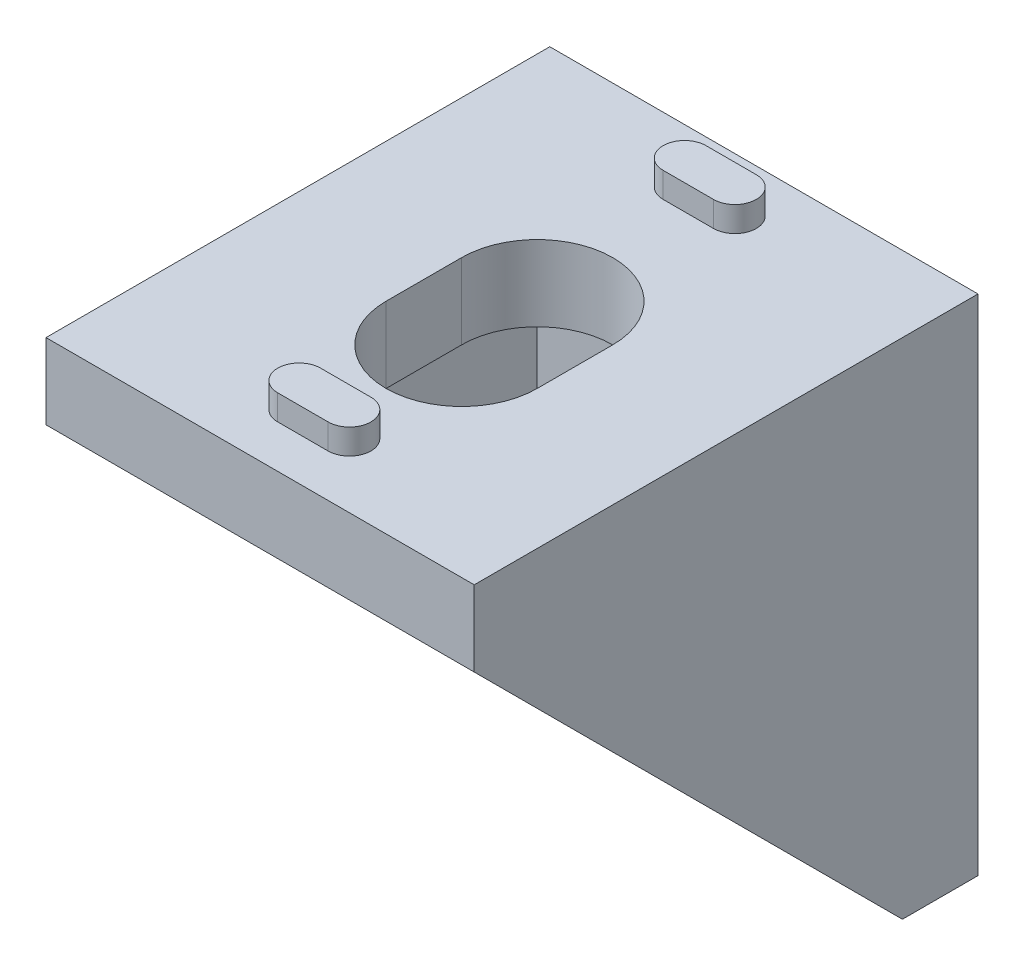
SolidWorks part; units mm, degrees
material "1060 Alloy"
ref_plane "Front Plane" through (0, 0, 0) normal (0, 0, 1) x (1, 0, 0)
ref_plane "Top Plane" through (0, 0, 0) normal (0, 1, 0) x (1, 0, 0)
ref_plane "Right Plane" through (0, 0, 0) normal (1, 0, 0) x (0, 0, -1)
sketch "Sketch1" plane through (0, 0, 0) normal (1, 0, 0) x (0, 0, -1)
  line L0 (0, 0) -> (-20, 0)
  line L1 (-20, 0) -> (-20, -3)
  line L2 (-20, -3) -> (-11.5, -11.5)
  line L3 (-11.5, -11.5) -> (0, 0) construction
  line L4 (-3, -20) -> (-11.5, -11.5)
  line L5 (0, -20) -> (-3, -20)
  line L6 (0, 0) -> (0, -20)
  dimension "D1" = 3
  dimension "D2" = 20
extrude "Boss-Extrude1" add sketch "Sketch1" along normal mid plane 17
sketch "Sketch2" plane through (0, 0, 0) normal (1, 0, 0) x (0, 0, -1)
  line L0 (-20, -3) -> (-3, -20) construction
  line L1 (-3, -3) -> (-20, -3)
  line L2 (-3, -3) -> (-3, -20)
  line L3 (-3, -20) -> (-20, -20)
  line L4 (-20, -3) -> (-20, -20)
  line L5 (-20, 0) -> (-20, -3) construction
extrude "Cut-Extrude1" cut sketch "Sketch2" against normal mid plane 12
sketch "Sketch3" plane through (0, 0, 3) normal (0, 0, 1) x (1, 0, 0)
  line L0 (0, -9) -> (0, -12) construction
  line L1 (-3, -9) -> (-3, -12)
  line L2 (3, -9) -> (3, -12)
  line L3 (0, -10.5) -> (0.7454, -10.5) construction
  line L4 (-6, -20) -> (6, -20) construction
  arc A0 (-3, -9) -> (3, -9) centre (0, -9) cw
  arc A1 (-3, -12) -> (3, -12) centre (0, -12) ccw
  dimension "D3" = 9
  dimension "D4" = 5
  dimension "D1" = 3
  dimension "D2" = 3
extrude "Cut-Extrude2" cut sketch "Sketch3" against normal up to next
sketch "Sketch4" plane through (0, 0, 0) normal (0, 0, -1) x (-1, 0, 0)
  line L0 (-1, -2.15) -> (1, -2.15) construction
  line L1 (-1, -3) -> (1, -3)
  line L2 (-1, -1.3) -> (1, -1.3)
  line L3 (0, 0) -> (0, -2.15) construction
  line L4 (-8.5, 0) -> (8.5, 0) construction
  line L5 (-2.1032, -9.8) -> (3, -9.8) construction
  line L6 (-1, -18.3) -> (1, -18.3)
  line L7 (-1, -16.6) -> (1, -16.6)
  line L8 (3, -12) -> (3, -9) construction
  arc A0 (-1, -3) -> (-1, -1.3) centre (-1, -2.15) cw
  arc A1 (1, -3) -> (1, -1.3) centre (1, -2.15) ccw
  arc A2 (1, -16.6) -> (1, -18.3) centre (1, -17.45) cw
  arc A3 (-1, -16.6) -> (-1, -18.3) centre (-1, -17.45) ccw
  dimension "D3" = 3.7
  dimension "D4" = 3
  dimension "D5" = 17
  dimension "D1" = 0.85
  dimension "D2" = 0.85
extrude "Boss-Extrude2" add sketch "Sketch4" along normal blind 1
ref_plane "Plane1" through (0, 0, 0) normal (0, 0.7071, 0.7071) x (-1, 0, 0)
mirror "Mirror1" about plane through (0, 0, 0) normal (0, 0.7071, 0.7071) of "Boss-Extrude2", "Cut-Extrude2"
